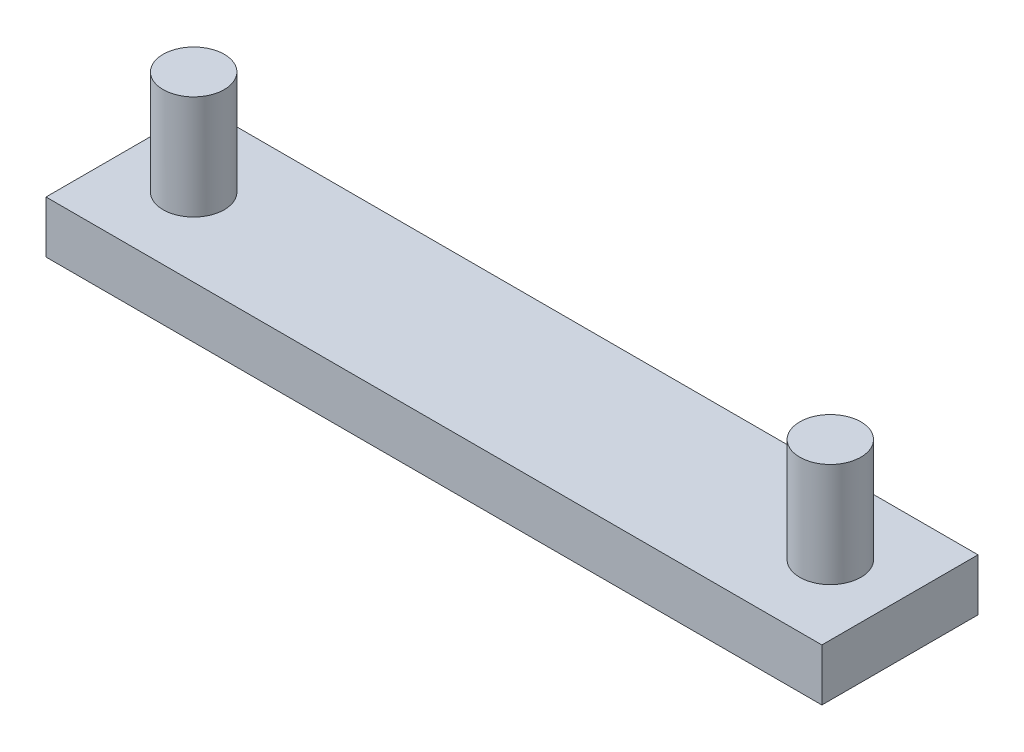
SolidWorks part; units mm, degrees
ref_plane "Front Plane" through (0, 0, 0) normal (0, 0, 1) x (1, 0, 0)
ref_plane "Top Plane" through (0, 0, 0) normal (0, 1, 0) x (1, 0, 0)
ref_plane "Right Plane" through (0, 0, 0) normal (1, 0, 0) x (0, 0, -1)
sketch "Sketch1" plane through (0, 0, 0) normal (0, 1, 0) x (1, 0, 0)
  line L0 (29.86, 0) -> (67.96, 0)
  line L1 (67.96, 0) -> (67.96, 76.2)
  line L2 (67.96, 0) -> (67.96, -76.2)
  line L3 (0, 0) -> (-621.47, 0)
  line L4 (-651.33, 0) -> (-689.43, 0)
  line L5 (-689.43, 0) -> (-689.43, 76.2)
  line L7 (-689.43, 76.2) -> (67.96, 76.2)
  line L8 (-689.43, 76.2) -> (-689.43, -76.2)
  line L9 (-689.43, -76.2) -> (67.96, -76.2)
  line L10 (67.96, 76.2) -> (67.96, -76.2)
  circle A0 centre (0, 0) radius 29.86
  circle A1 centre (-621.47, 0) radius 29.86
  dimension "D1" = 59.72
  dimension "D6" = 59.72
  dimension "D3" = 76.2
  dimension "D4" = 38.1
  dimension "D5" = 621.47
  dimension "D7" = 38.1
  dimension "D8" = 76.2
extrude "Boss-Extrude1" add sketch "Sketch1" along normal blind 50.8 contours A1 L4 L8 L9 L2 L0 A0 L3 | A1 L3 A0 L0 L1 L7 L5 L4
sketch "Sketch2" plane through (0, 0, 0) normal (0, -1, 0) x (1, 0, 0)
  circle A0 centre (0, 0) radius 29.86 construction
  circle A1 centre (0, 0) radius 29.86
  circle A2 centre (-621.47, 0) radius 29.86 construction
  circle A3 centre (-621.47, 0) radius 29.86
extrude "Boss-Extrude2" add sketch "Sketch2" against normal blind 152.4
